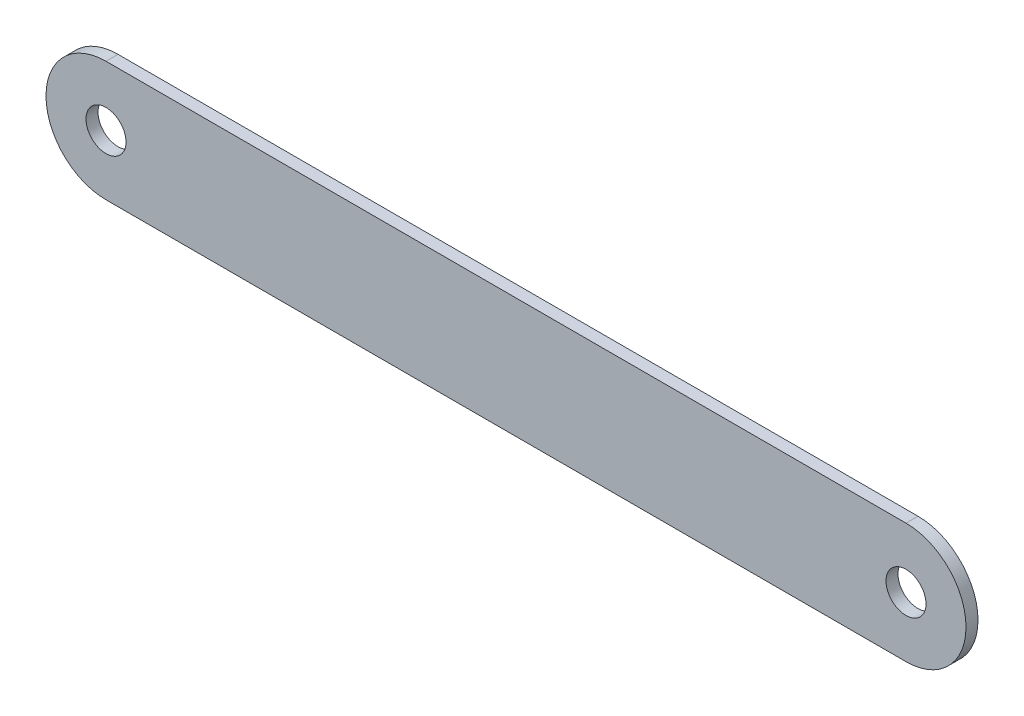
SolidWorks part; units mm, degrees
ref_plane "Front Plane" through (0, 0, 0) normal (0, 0, 1) x (1, 0, 0)
ref_plane "Top Plane" through (0, 0, 0) normal (0, 1, 0) x (1, 0, 0)
ref_plane "Right Plane" through (0, 0, 0) normal (1, 0, 0) x (0, 0, -1)
sketch "Sketch1" plane through (0, 0, 0) normal (0, 0, 1) x (1, 0, 0)
  line L0 (0, 0) -> (200, 0) construction
  line L1 (0, 15) -> (200, 15)
  line L2 (0, -15) -> (200, -15)
  circle A0 centre (0, 0) radius 5
  circle A1 centre (200, 0) radius 5
  arc A2 (0, 15) -> (0, -15) centre (0, 0) ccw
  arc A3 (200, 15) -> (200, -15) centre (200, 0) cw
  dimension "D1" = 10
  dimension "D3" = 10
  dimension "D4" = 10
  dimension "D5" = 10
  dimension "D2" = 200
extrude "Boss-Extrude1" add sketch "Sketch1" along normal blind 3
